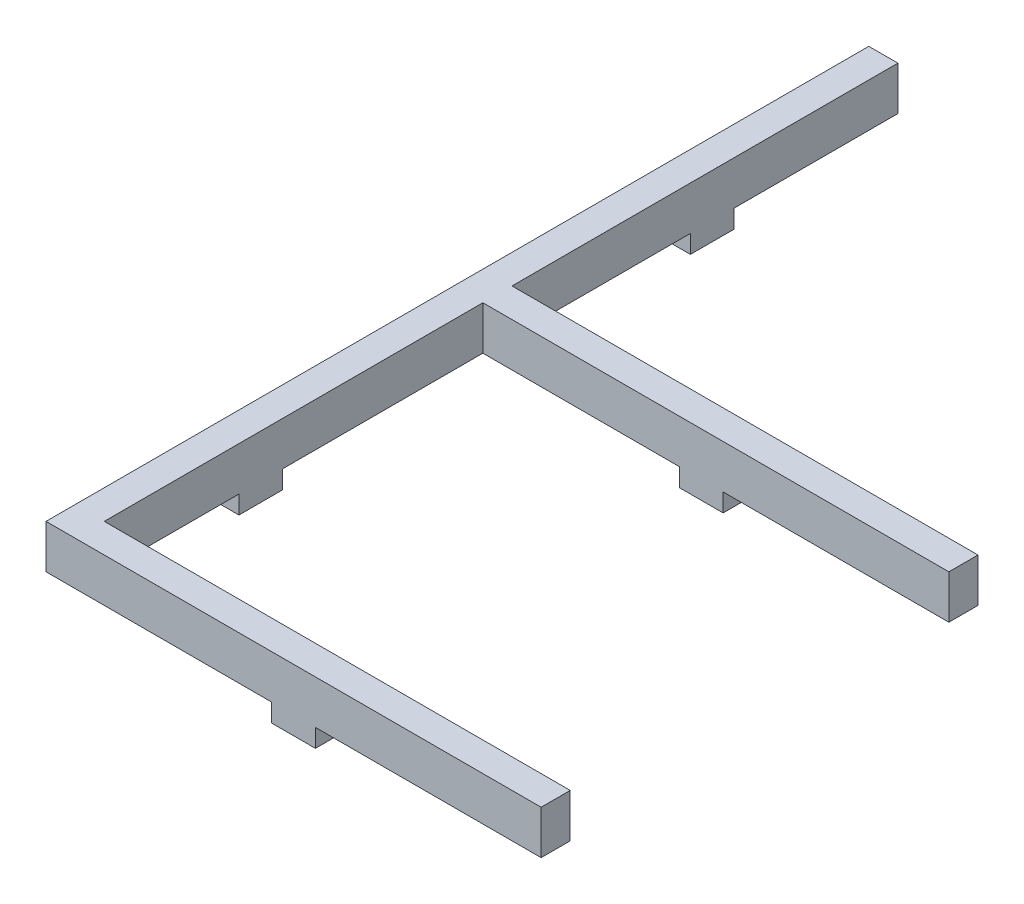
SolidWorks part; units mm, degrees
ref_plane "Plano frontal" through (0, 0, 0) normal (0, 0, 1) x (1, 0, 0)
ref_plane "Plano superior" through (0, 0, 0) normal (0, 1, 0) x (1, 0, 0)
ref_plane "Plano direito" through (0, 0, 0) normal (1, 0, 0) x (0, 0, -1)
sketch "Esboço1" plane through (0, 0, 0) normal (0, 1, 0) x (1, 0, 0)
  line L0 (0, -28) -> (0, -2)
  line L1 (0, 0) -> (32, 0)
  line L2 (0, -28) -> (32, -28)
  line L3 (-2, 26.5) -> (-2, -30)
  line L4 (0, -2) -> (32, -2)
  line L5 (-2, -30) -> (32, -30)
  line L6 (32, -30) -> (32, -28)
  line L7 (32, 0) -> (32, -2)
  line L8 (-2, 26.5) -> (0, 26.5)
  line L9 (0, 0) -> (0, 26.5)
  point P3 (0, 0)
  point P4 (0, 0)
  point P12 (0, 0)
  dimension "D1" = 26
  dimension "D2" = 28.5
  dimension "D3" = 2
  dimension "D5" = 2
  dimension "D6" = 32
  dimension "D4" = 2
extrude "Ressalto-extrusão1" add sketch "Esboço1" along normal blind 3
sketch "Esboço3" plane through (-2, 0, 0) normal (-1, 0, 0) x (0, 0, 1)
  line L0 (1.75, 3) -> (1.75, 0) construction
  line L1 (-26.5, 0) -> (30, 0) construction
  line L2 (-15.25, 0) -> (-12.25, 0)
  line L3 (-15.25, 0) -> (-15.25, -1.25)
  line L4 (-15.25, -1.25) -> (-12.25, -1.25)
  line L5 (-12.25, 0) -> (-12.25, -1.25)
  line L6 (-26.5, 3) -> (30, 3) construction
  line L7 (15.75, 0) -> (15.75, -1.25)
  line L8 (18.75, -1.25) -> (15.75, -1.25)
  line L9 (18.75, 0) -> (18.75, -1.25)
  line L10 (18.75, 0) -> (15.75, 0)
  dimension "D1" = 1.25
  dimension "D2" = 3
  dimension "D3" = 14
extrude "Ressalto-extrusão2" add sketch "Esboço3" against normal up to surface (2 mm away) up to face at (0, 1.5, 15)
sketch "Esboço4" plane through (0, 0, 30) normal (0, 0, 1) x (1, 0, 0)
  line L0 (15, 0) -> (15, 3) construction
  line L1 (-2, 0) -> (32, 0) construction
  line L2 (-2, 3) -> (32, 3) construction
  line L4 (16.5, -1.25) -> (13.5, -1.25)
  line L5 (16.5, -1.25) -> (16.5, 0)
  line L6 (16.5, 0) -> (13.5, 0)
  line L7 (13.5, -1.25) -> (13.5, 0)
  line L8 (16.5, -1.25) -> (13.5, 0) construction
  line L9 (16.5, 0) -> (13.5, -1.25) construction
  point P6 (15, -0.625)
  point P11 (0, 0)
  dimension "D1" = 1.25
  dimension "D2" = 3
extrude "Ressalto-extrusão3" add sketch "Esboço4" against normal blind 2
ref_plane "Plano1" through (0, 0, 15) normal (0, 0, 1) x (1, 0, 0)
mirror "Espelhar1" about plane through (0, 0, 15) normal (0, 0, 1) of "Ressalto-extrusão3"
